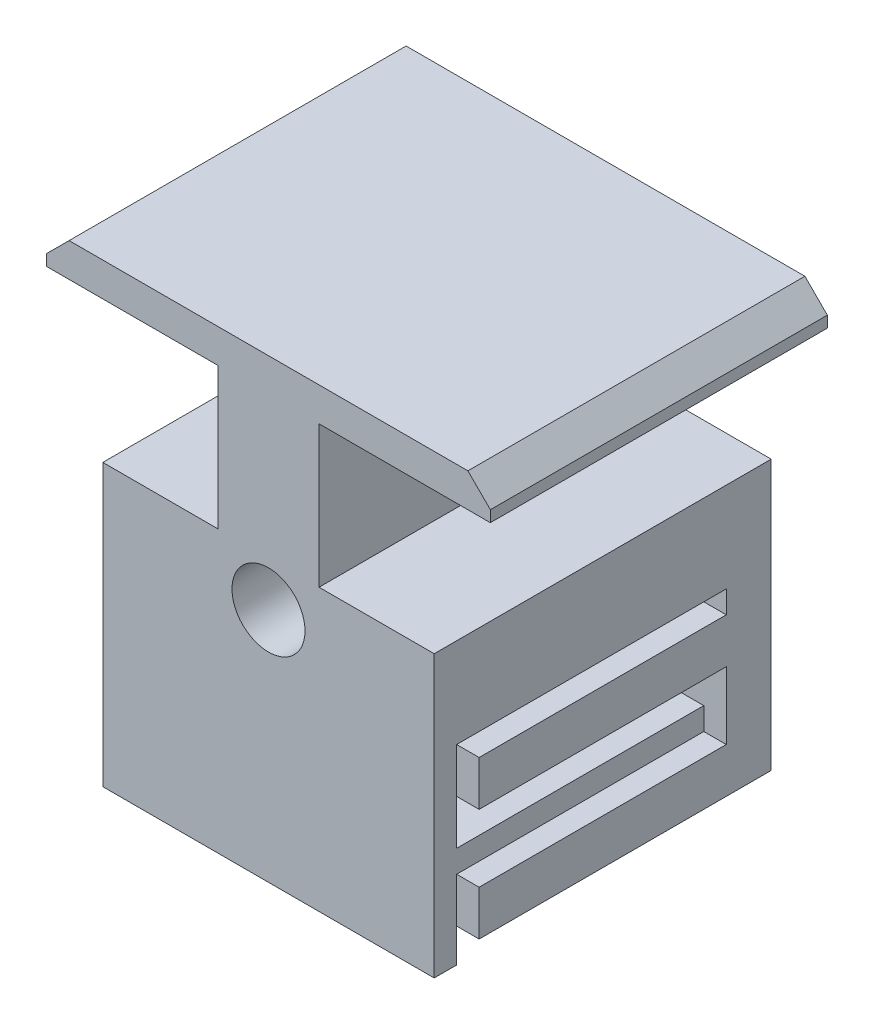
SolidWorks part; units mm, degrees
ref_plane "Front Plane" through (0, 0, 0) normal (0, 0, 1) x (1, 0, 0)
ref_plane "Top Plane" through (0, 0, 0) normal (0, 1, 0) x (1, 0, 0)
ref_plane "Right Plane" through (0, 0, 0) normal (1, 0, 0) x (0, 0, -1)
sketch "Sketch1" plane through (0, 0, 0) normal (0, 0, 1) x (1, 0, 0)
  line L0 (0, 0) -> (-10.25, 0)
  line L2 (-10.25, -3) -> (0, -3)
  line L3 (0, -3) -> (0, -15.6)
  line L4 (0, -15.6) -> (-10.25, -15.6)
  line L5 (-10.25, -15.6) -> (-10.25, -40.6)
  line L6 (19.25, -3) -> (24.25, -3)
  line L7 (19.25, -40.6) -> (4.5, -40.6) construction
  line L8 (4.5, -40.6) -> (4.5, -32.011) construction
  line L9 (0, 0) -> (9, 0)
  line L10 (19.25, -40.6) -> (-10.25, -40.6)
  line L11 (9, 0) -> (19.25, 0)
  line L13 (19.25, -3) -> (9, -3)
  line L14 (9, -3) -> (9, -15.6)
  line L15 (9, -15.6) -> (19.25, -15.6)
  line L16 (19.25, -15.6) -> (19.25, -40.6)
  line L17 (24.25, -3) -> (24.25, 0)
  line L18 (24.25, 0) -> (19.25, 0)
  line L19 (-10.25, 0) -> (-15.25, 0)
  line L20 (-15.25, 0) -> (-15.25, -3)
  line L21 (-15.25, -3) -> (-10.25, -3)
  point P12 (4.5, 0)
  dimension "D1" = 3
  dimension "D2" = 12.6
  dimension "D3" = 25
  dimension "D4" = 29.5
  dimension "D5" = 4.5
  dimension "D6" = 5
  dimension "D7" = 5
extrude "Boss-Extrude1" add sketch "Sketch1" along normal blind 30
sketch "Sketch2" plane through (0, 0, 30) normal (0, 0, 1) x (1, 0, 0)
  line L0 (9, -15.6) -> (0, -15.6) construction
  line L1 (4.5, -15.6) -> (4.5, -19.6) construction
  circle A0 centre (4.5, -19.6) radius 3.25
  dimension "D2" = 6.5
  dimension "D1" = 4
extrude "Cut-Extrude1" cut sketch "Sketch2" against normal blind 36
sketch "Sketch3" plane through (19.25, 0, 0) normal (1, 0, 0) x (0, 0, -1)
  line L0 (0, -39.6) -> (-26, -39.6)
  line L1 (0, -40.6) -> (0, -15.6) construction
  line L2 (-26, -39.6) -> (-26, -35.6)
  line L3 (-26, -35.6) -> (-4, -35.6)
  line L4 (-4, -35.6) -> (-4, -29.6)
  line L5 (-4, -29.6) -> (-26, -29.6)
  line L6 (-26, -29.6) -> (-26, -25.6)
  line L7 (-26, -25.6) -> (-4, -25.6)
  line L8 (-30, -40.6) -> (0, -40.6) construction
  line L9 (-30, -40.6) -> (-30, -15.6) construction
  point P14 (-30, -28.1)
  dimension "D1" = 6
  dimension "D2" = 4
  dimension "D3" = 1
  dimension "D4" = 4
  dimension "D5" = 4
extrude "Cut-Extrude-Thin1" cut sketch "Sketch3" against normal up to vertex (19.25 mm away) and the other way through all thin up to point (0, -15.6, 0) thin type one direction reverse wall 2
chamfer "Chamfer2" distance 2 angle 45 2 edges at (24.25, 0, 15) (-15.25, 0, 15)
